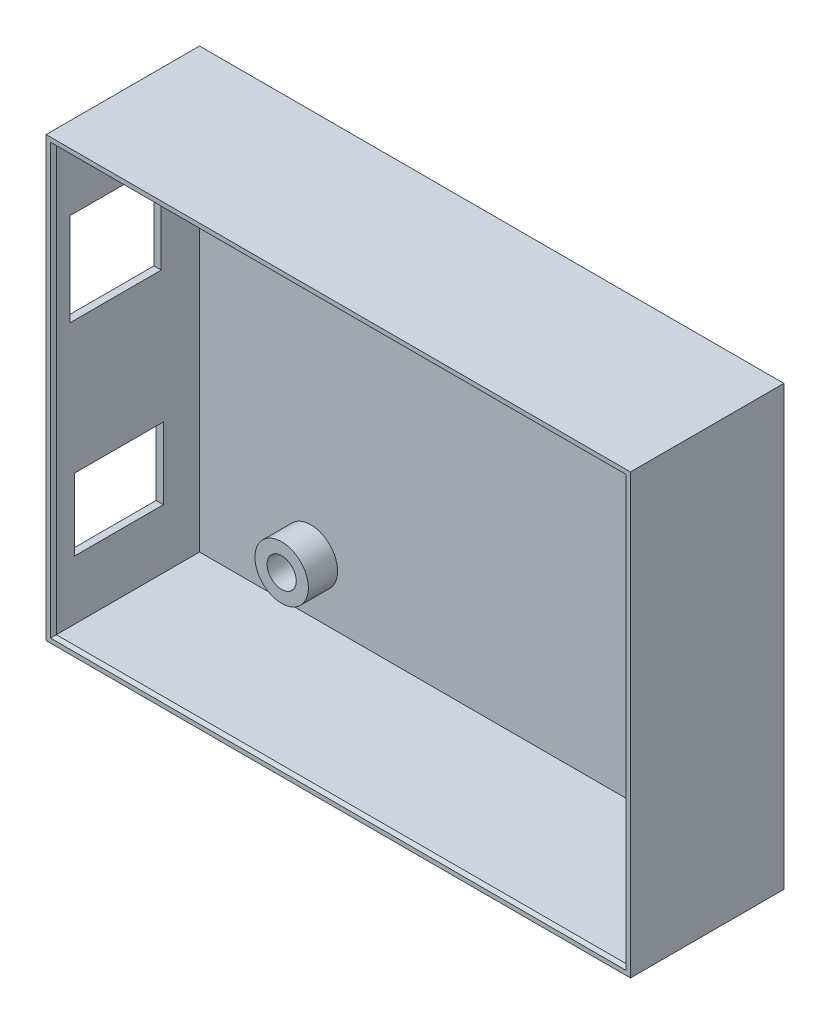
SolidWorks part; units mm, degrees
ref_plane "Спереди" through (0, 0, 0) normal (0, 0, 1) x (1, 0, 0)
ref_plane "Сверху" through (0, 0, 0) normal (0, 1, 0) x (1, 0, 0)
ref_plane "Справа" through (0, 0, 0) normal (1, 0, 0) x (0, 0, -1)
sketch "Эскиз1" plane through (0, 0, 0) normal (0, 0, 1) x (1, 0, 0)
  line L1 (-21.978, 29.6703) -> (58.022, 29.6703)
  line L2 (-21.978, 29.6703) -> (-21.978, -30.3297)
  line L3 (-21.978, -30.3297) -> (58.022, -30.3297)
  line L4 (58.022, 29.6703) -> (58.022, -30.3297)
  dimension "D1" = 60
  dimension "D2" = 80
extrude "Бобышка-Вытянуть1" add sketch "Эскиз1" along normal blind 2
sketch "Эскиз2" plane through (0, 0, 2) normal (0, 0, 1) x (1, 0, 0)
  line L0 (-20.978, 28.6703) -> (-20.978, -29.3297)
  line L1 (-20.978, -29.3297) -> (57.022, -29.3297)
  line L2 (57.022, -29.3297) -> (57.022, 28.6703)
  line L3 (57.022, 28.6703) -> (-20.978, 28.6703)
  line L4 (-21.978, 29.6703) -> (-21.978, -30.3297)
  line L5 (-21.978, -30.3297) -> (58.022, -30.3297)
  line L6 (58.022, -30.3297) -> (58.022, 29.6703)
  line L7 (58.022, 29.6703) -> (-21.978, 29.6703)
  line L8 (-21.978, 29.6703) -> (-21.978, -30.3297)
  line L9 (-21.978, -30.3297) -> (58.022, -30.3297)
  line L10 (58.022, -30.3297) -> (58.022, 29.6703)
  line L11 (58.022, 29.6703) -> (-21.978, 29.6703)
  dimension "D1" = 0
  dimension "D2" = 1
extrude "Бобышка-Вытянуть2" add sketch "Эскиз2" along normal blind 20
chamfer "Фаска1" distance 1 angle 45 4 edges at (18.022, -30.3297, 0) (58.022, -0.3297, 0) (18.022, 29.6703, 0) (-21.978, -0.3297, 0)
sketch "Эскиз3" plane through (-21.978, 0, 0) normal (-1, 0, 0) x (0, 0, 1)
  line L0 (7.94, 7.0203) -> (18.24, 7.0203) construction
  line L1 (7.54, 19.1203) -> (19.4296, 19.1203) construction
  line L2 (7.54, 19.1203) -> (7.54, 7.0203) construction
  line L3 (7.54, 7.0203) -> (19.4296, 7.0203) construction
  line L4 (19.4296, 19.1203) -> (19.4296, 7.0203) construction
  line L5 (7.24, 19.4203) -> (19.7296, 19.4203)
  line L6 (7.249, -11.7233) -> (18.8175, -11.7233) construction
  line L7 (7.249, -11.7233) -> (7.249, -20.9394) construction
  line L8 (7.249, -20.9394) -> (18.8175, -20.9394) construction
  line L9 (18.8175, -11.7233) -> (18.8175, -20.9394) construction
  line L10 (19.7296, 19.4203) -> (19.7296, 6.7203)
  line L11 (7.24, 6.7203) -> (19.7296, 6.7203)
  line L12 (7.24, 19.4203) -> (7.24, 6.7203)
  line L13 (6.949, -11.4233) -> (19.1175, -11.4233)
  line L14 (19.1175, -11.4233) -> (19.1175, -21.2394)
  line L15 (6.949, -21.2394) -> (19.1175, -21.2394)
  line L16 (6.949, -11.4233) -> (6.949, -21.2394)
  dimension "D1" = 0.3
extrude "Вырез-Вытянуть1" cut sketch "Эскиз3" against normal blind 10
sketch "Эскиз4" plane through (0, 0, 2) normal (0, 0, 1) x (1, 0, 0)
  circle A0 centre (-5.7491, 26.1217) radius 2
  circle A1 centre (45.2709, 10.8627) radius 2
  circle A2 centre (45.2854, -17.0586) radius 2
  circle A3 centre (-5.7328, -22.1382) radius 2
  circle A4 centre (-5.7491, 26.1217) radius 3.4314
  circle A5 centre (45.2709, 10.8627) radius 3.3125
  circle A6 centre (45.2854, -17.0586) radius 3.8677
  circle A7 centre (-5.7328, -22.1382) radius 3.6606
  dimension "D1" = 4
extrude "Бобышка-Вытянуть4" add sketch "Эскиз4" along normal blind 4
chamfer "Фаска2" distance 0.4 angle 45 4 edges at (18.022, -29.3297, 22) (57.022, -0.3297, 22) (-20.978, -0.3297, 22) (18.022, 28.6703, 22)
